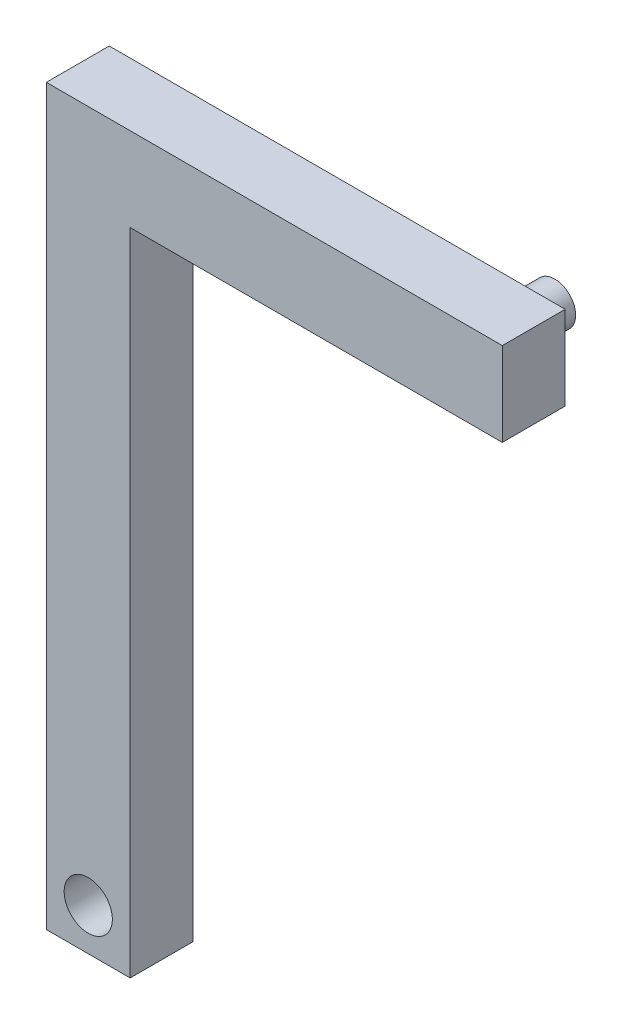
SolidWorks part; units mm, degrees
ref_plane "Alzado" through (0, 0, 0) normal (0, 0, 1) x (1, 0, 0)
ref_plane "Planta" through (0, 0, 0) normal (0, 1, 0) x (1, 0, 0)
ref_plane "Vista lateral" through (0, 0, 0) normal (1, 0, 0) x (0, 0, -1)
sketch "Croquis1" plane through (0, 0, 0) normal (0, 0, 1) x (1, 0, 0)
  line L1 (0, 0) -> (22.5, 0)
  line L2 (0, 0) -> (0, -4)
  line L3 (0, -4) -> (22.5, -4)
  line L4 (22.5, 0) -> (22.5, -4)
  circle A0 centre (3.5, -2) radius 1.05
  dimension "D5" = 2.1
  dimension "D1" = 4
  dimension "D2" = 22.5
  dimension "D3" = 19
  dimension "D4" = 2
extrude "Saliente-Extruir1" add sketch "Croquis1" along normal blind 3 contours L1 L4 L3 L2
sketch "Croquis3" plane through (0, 0, 0) normal (0, 0, -1) x (-1, 0, 0)
  line L0 (0, 0) -> (0, -4) construction
  line L1 (0, 0) -> (-22.5, 0) construction
  circle A0 centre (-20, -2) radius 1
  dimension "D3" = 2
  dimension "D1" = 20
  dimension "D2" = 2
sketch "Croquis4" plane through (0, 0, 3) normal (0, 0, 1) x (1, 0, 0)
  line L0 (0, 0) -> (22.5, 0) construction
  circle A0 centre (2.25, -2) radius 1.05
  dimension "D2" = 2.1
  dimension "D3" = 2
extrude "Saliente-Extruir2" add sketch "Croquis3" along normal blind 2
sketch "Croquis5" plane through (0, 0, 0) normal (0, 0, -1) x (-1, 0, 0)
  line L0 (0, -4) -> (-22.5, -4) construction
  line L1 (-4.75, -4) -> (-0.75, -4)
  line L2 (-4.75, -4) -> (-4.75, -35)
  line L3 (-4.75, -35) -> (-0.75, -35)
  line L4 (-0.75, -4) -> (-0.75, -35)
  line L5 (0, 0) -> (-22.5, 0) construction
  circle A0 centre (-20, -2) radius 1 construction
  circle A2 centre (-2.75, -33) radius 1.05
  dimension "D1" = 2
  dimension "D4" = 2.1
  dimension "D5" = 2
  dimension "D6" = 17.25
  dimension "D3" = 35
  dimension "D2" = 4
extrude "Saliente-Extruir3" add sketch "Croquis5" against normal blind 3
sketch "Croquis7" plane through (0, 0, 0) normal (0, 0, -1) x (-1, 0, 0)
  circle A0 centre (-2.75, 24.5) radius 1
  circle A2 centre (-20, -2) radius 1 construction
  dimension "D1" = 17.25
sketch "Croquis10" plane through (0, 0, 3) normal (0, 0, 1) x (1, 0, 0)
  line L1 (0.75, -4) -> (-0.4142, -4)
  line L2 (0.75, -4) -> (0.75, 0.5775)
  line L3 (0.75, 0.5775) -> (-0.4142, 0.5775)
  line L4 (-0.4142, -4) -> (-0.4142, 0.5775)
extrude "Cortar-Extruir4" cut sketch "Croquis10" against normal through all
sketch "Croquis12" plane through (0, 0, 0) normal (0, 0, -1) x (-1, 0, 0)
  circle A0 centre (-2.75, -33) radius 1.15
  dimension "D1" = 2.3
extrude "Cortar-Extruir5" cut sketch "Croquis12" against normal through all
